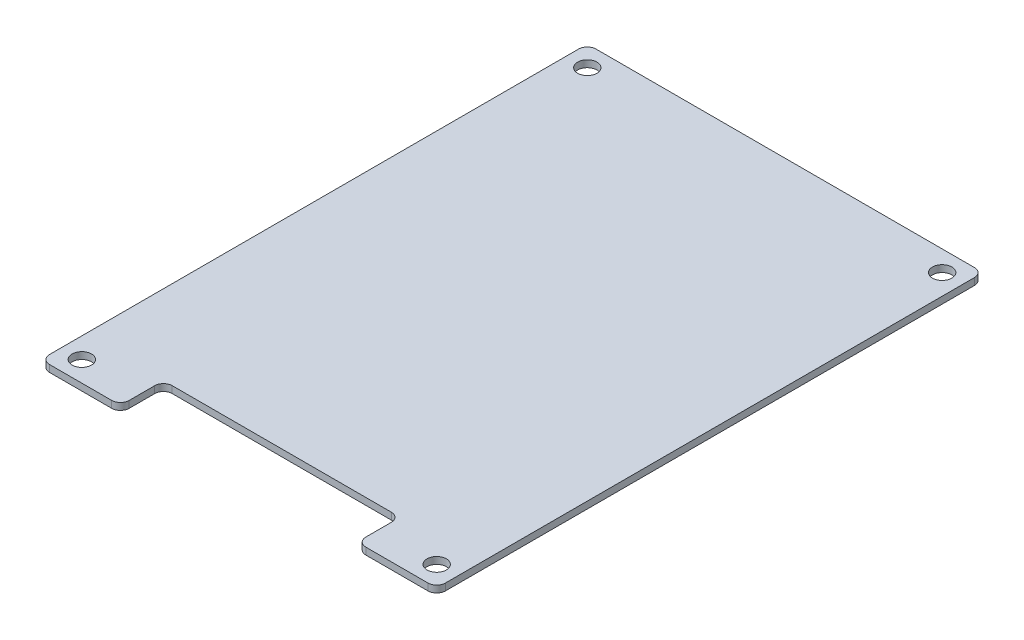
SolidWorks part; units mm, degrees
ref_plane "Front" through (0, 0, 0) normal (0, 0, 1) x (1, 0, 0)
ref_plane "Top" through (0, 0, 0) normal (0, 1, 0) x (1, 0, 0)
ref_plane "Right" through (0, 0, 0) normal (1, 0, 0) x (0, 0, -1)
sketch "Sketch1" plane through (0, 0, 0) normal (0, 1, 0) x (1, 0, 0)
  line L1 (-46, -63.5) -> (46, -63.5)
  line L2 (-46, -63.5) -> (-46, 63.5)
  line L3 (-46, 63.5) -> (46, 63.5)
  line L4 (46, -63.5) -> (46, 63.5)
  line L5 (-46, -63.5) -> (46, 63.5) construction
  line L6 (-46, 63.5) -> (46, -63.5) construction
  point P0 (0, 0)
  dimension "D1" = 127
  dimension "D2" = 92
extrude "Boss-Extrude1" add sketch "Sketch1" along normal blind 1.6
hole_wizard "M4 Clearance Hole1" positions "Sketch2" profile "Sketch3" hole size "M4" standard "ANSI Metric"
sketch "Sketch2" plane through (0, 1.6, 0) normal (0, 1, 0) x (1, 0, 0)
  line L1 (-41.2375, 58.7375) -> (41.2375, 58.7375)
  line L2 (-41.2375, 58.7375) -> (-41.2375, -58.7375)
  line L3 (-41.2375, -58.7375) -> (41.2375, -58.7375)
  line L4 (41.2375, 58.7375) -> (41.2375, -58.7375)
  line L5 (-41.2375, 58.7375) -> (41.2375, -58.7375) construction
  line L6 (-41.2375, -58.7375) -> (41.2375, 58.7375) construction
  line L7 (46, -63.5) -> (46, 63.5) construction
  line L8 (-46, -63.5) -> (46, -63.5) construction
  point P0 (-41.2375, 58.7375)
  point P2 (41.2375, 58.7375)
  point P4 (41.2375, -58.7375)
  point P6 (-41.2375, -58.7375)
  dimension "D1" = 4.7625
  dimension "D2" = 4.7625
sketch "Sketch3" plane through (-41.2375, 1.6, -58.7375) normal (1, 0, 0) x (0, 0, 1)
  line L0 (0, 0) -> (0, 51.3519)
  line L1 (0, 51.3519) -> (2.25, 50)
  line L2 (2.25, 50) -> (2.25, 0)
  line L5 (2.25, 0) -> (0, 0)
  line L10 (0, 51.3519) -> (-2.25, 50) construction
  line L11 (0, -6.35) -> (0, 107.95) construction
  dimension "Hole Dia." = 4.5
  dimension "Hole Depth" = 50
  dimension "Drill Angle" = 118
sketch "Sketch4" plane through (0, 1.6, 0) normal (0, 1, 0) x (1, 0, 0)
  line L0 (-46, -63.5) -> (46, -63.5) construction
  line L1 (-27.5, -53.5) -> (27.5, -53.5)
  line L2 (-27.5, -53.5) -> (-27.5, -63.5)
  line L3 (-27.5, -63.5) -> (27.5, -63.5)
  line L4 (27.5, -53.5) -> (27.5, -63.5)
  line L5 (-27.5, -53.5) -> (27.5, -63.5) construction
  line L6 (-27.5, -63.5) -> (27.5, -53.5) construction
  line L7 (-46, -63.5) -> (0, -58.5) construction
  line L8 (0, -58.5) -> (46, -63.5) construction
  point P0 (0, -58.5)
  dimension "D1" = 55
  dimension "D2" = 10
extrude "Cut-Extrude1" cut sketch "Sketch4" against normal blind 1.6
fillet "Fillet1" radius 2.032 8 edges at (-46, 0.8, -63.5) (46, 0.8, -63.5) (46, 0.8, 63.5) (27.5, 0.8, 63.5) (27.5, 0.8, 53.5) (-46, 0.8, 63.5) (-27.5, 0.8, 63.5) (-27.5, 0.8, 53.5)
